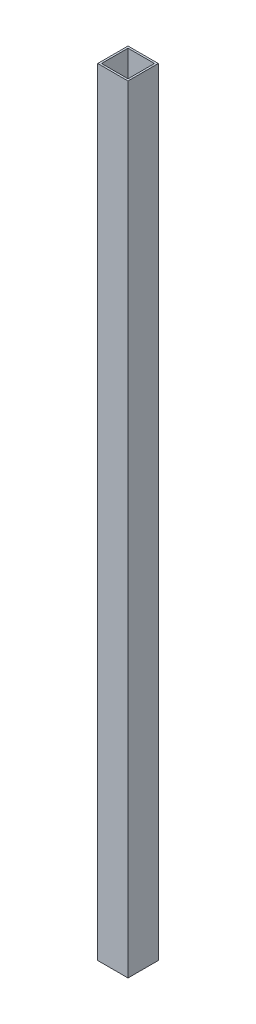
SolidWorks part; units mm, degrees
ref_plane "Front Plane" through (0, 0, 0) normal (0, 0, 1) x (1, 0, 0)
ref_plane "Top Plane" through (0, 0, 0) normal (0, 1, 0) x (1, 0, 0)
ref_plane "Right Plane" through (0, 0, 0) normal (1, 0, 0) x (0, 0, -1)
sketch "Sketch1" plane through (0, 0, 0) normal (0, 1, 0) x (1, 0, 0)
  line L1 (-25.4, 25.4) -> (25.4, 25.4)
  line L2 (-25.4, 25.4) -> (-25.4, -25.4)
  line L3 (-25.4, -25.4) -> (25.4, -25.4)
  line L4 (25.4, 25.4) -> (25.4, -25.4)
  line L5 (-25.4, 25.4) -> (25.4, -25.4) construction
  line L6 (-25.4, -25.4) -> (25.4, 25.4) construction
  line L7 (-22.225, 22.225) -> (22.225, 22.225)
  line L8 (-22.225, 22.225) -> (-22.225, -22.225)
  line L9 (-22.225, -22.225) -> (22.225, -22.225)
  line L10 (22.225, 22.225) -> (22.225, -22.225)
  line L11 (-22.225, 22.225) -> (22.225, -22.225) construction
  line L12 (-22.225, -22.225) -> (22.225, 22.225) construction
  point P0 (0, 0)
  point P6 (0, 0)
  dimension "D1" = 50.8
  dimension "D2" = 3.175
extrude "Boss-Extrude1" add sketch "Sketch1" along normal blind 1303.57
